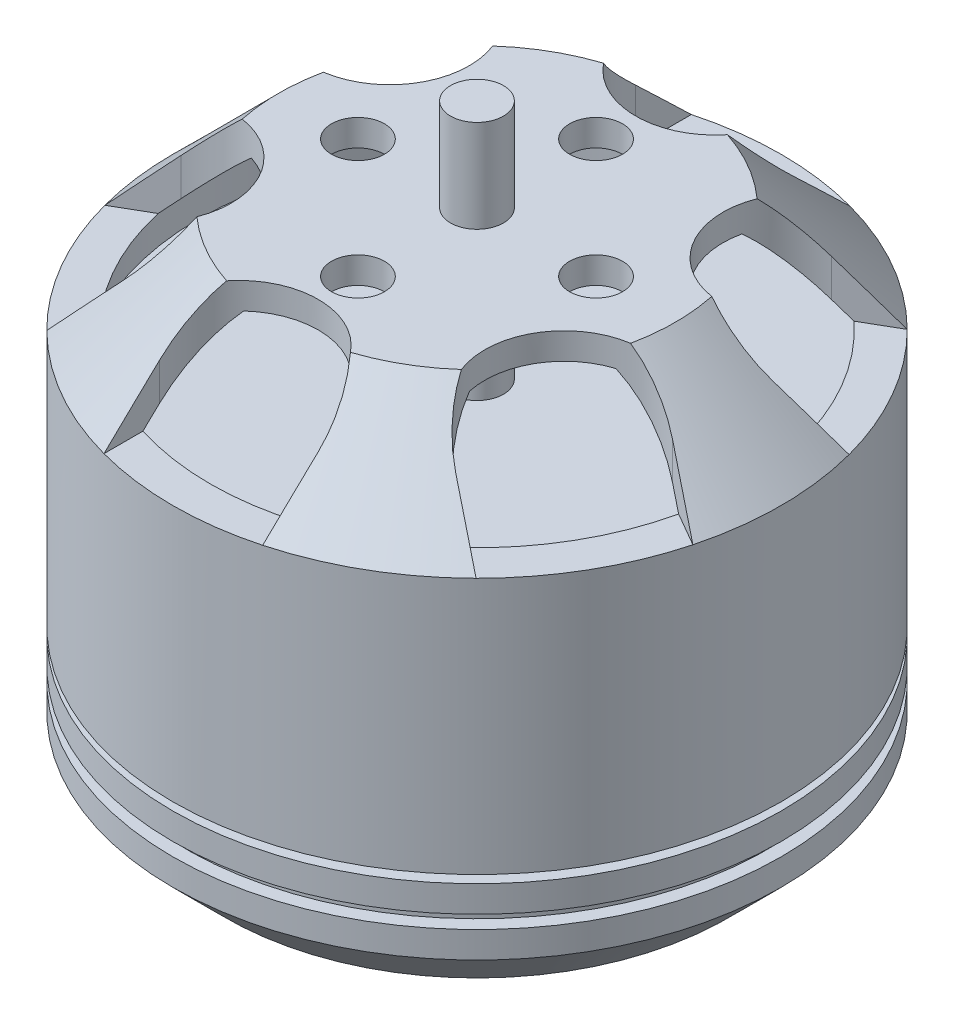
SolidWorks part; units mm, degrees
ref_plane "Front Plane" through (0, 0, 0) normal (0, 0, 1) x (1, 0, 0)
ref_plane "Top Plane" through (0, 0, 0) normal (0, 1, 0) x (1, 0, 0)
ref_plane "Right Plane" through (0, 0, 0) normal (1, 0, 0) x (0, 0, -1)
sketch "Sketch1" plane through (0, 0, 0) normal (0, 0, 1) x (1, 0, 0)
  line L0 (0, 18.8614) -> (0, 0)
  line L1 (1, -3.1386) -> (9.5, -3.1386)
  line L2 (9.5, -3.1386) -> (11.5, -1.1386)
  line L3 (11.5, -1.1386) -> (11.5, -0.1386)
  line L4 (11.5, 11.3614) -> (7.5, 15.3614)
  line L5 (7.5, 15.3614) -> (1, 15.3614)
  line L6 (1, 15.3614) -> (1, 18.8614)
  line L7 (1, 18.8614) -> (0, 18.8614)
  line L8 (0, 0) -> (0, -4.9386)
  line L9 (0, -4.9386) -> (1, -4.9386)
  line L10 (1, -4.9386) -> (1, -3.1386)
  line L11 (2, 14.3614) -> (7.0858, 14.3614)
  line L12 (7.0858, 14.3614) -> (10.5, 10.9472)
  line L13 (10.5, 10.9472) -> (10.5, 9.7543)
  line L14 (10.5, 9.7543) -> (1, 9.7543)
  line L15 (1, 9.7543) -> (1, 13.3614)
  line L16 (1, 13.3614) -> (2, 13.3614)
  line L17 (2, 13.3614) -> (2, 14.3614)
  line L18 (11.5, -0.1386) -> (11, -0.1386)
  line L19 (11, -0.1386) -> (11, 0.3614)
  line L20 (11, 0.3614) -> (11.5, 0.3614)
  line L21 (11.5, 1.3614) -> (9.5, 1.3614)
  line L22 (9.5, 1.3614) -> (9.5, 1.6614)
  line L23 (9.5, 1.6614) -> (11.5, 1.6614)
  line L24 (11.5, 1.6614) -> (11.5, 11.3614)
  line L25 (11.5, 0.3614) -> (11.5, 1.3614)
  dimension "D1" = 23.8
  dimension "D2" = 1.8
  dimension "D3" = 1
  dimension "D4" = 45
  dimension "D5" = 2
  dimension "D6" = 1
  dimension "D7" = 11.5
  dimension "D8" = 3.5
  dimension "D9" = 1
  dimension "D10" = 1
  dimension "D11" = 1
  dimension "D12" = 1
  dimension "D13" = 1
  dimension "D14" = 1
  dimension "D15" = 4
  dimension "D16" = 0.5
  dimension "D17" = 0.5
  dimension "D18" = 1
  dimension "D19" = 2
  dimension "D20" = 0.3
  dimension "D21" = 1
revolve "Revolve2" add sketch "Sketch1" angle 360 about L0
sketch "Sketch2" plane through (0, 15.3614, 0) normal (0, 1, 0) x (1, 0, 0)
  line L0 (0, 0) -> (0, 9) construction
  line L1 (-3, 9) -> (-3, 15.3921)
  line L2 (-3, 15.3921) -> (3, 15.3921)
  line L3 (3, 15.3921) -> (3, 9)
  line L4 (6.2942, 7.0981) -> (11.8299, 10.2941)
  line L5 (11.8299, 10.2941) -> (14.8299, 5.098)
  line L6 (14.8299, 5.098) -> (9.2942, 1.9019)
  line L7 (9.2942, -1.9019) -> (14.8299, -5.098)
  line L8 (14.8299, -5.098) -> (11.8299, -10.2941)
  line L9 (11.8299, -10.2941) -> (6.2942, -7.0981)
  line L10 (3, -9) -> (3, -15.3921)
  line L11 (3, -15.3921) -> (-3, -15.3921)
  line L12 (-3, -15.3921) -> (-3, -9)
  line L13 (-6.2942, -7.0981) -> (-11.8299, -10.2941)
  line L14 (-11.8299, -10.2941) -> (-14.8299, -5.098)
  line L15 (-14.8299, -5.098) -> (-9.2942, -1.9019)
  line L16 (-9.2942, 1.9019) -> (-14.8299, 5.098)
  line L17 (-14.8299, 5.098) -> (-11.8299, 10.2941)
  line L18 (-11.8299, 10.2941) -> (-6.2942, 7.0981)
  circle A0 centre (0, 0) radius 4.5 construction
  circle A1 centre (0, 0) radius 8.5 construction
  circle A2 centre (0, -4.5) radius 1
  circle A3 centre (-4.5, 0) radius 1
  circle A4 centre (0, 4.5) radius 1
  circle A5 centre (4.5, 0) radius 1
  arc A6 (-3, 9) -> (3, 9) centre (0, 9) ccw
  arc A7 (6.2942, 7.0981) -> (9.2942, 1.9019) centre (7.7942, 4.5) ccw
  arc A8 (9.2942, -1.9019) -> (6.2942, -7.0981) centre (7.7942, -4.5) ccw
  arc A9 (3, -9) -> (-3, -9) centre (0, -9) ccw
  arc A10 (-6.2942, -7.0981) -> (-9.2942, -1.9019) centre (-7.7942, -4.5) ccw
  arc A11 (-9.2942, 1.9019) -> (-6.2942, 7.0981) centre (-7.7942, 4.5) ccw
  point P17 (0, 0)
  point P47 (0, 0)
  dimension "D1" = 9
  dimension "D3" = 2
  dimension "D5" = 6
  dimension "D7" = 17
  dimension "D2" = 9
  dimension "D4" = 4
  dimension "D6" = 6
extrude "Cut-Extrude1" cut sketch "Sketch2" against normal blind 4
sketch "Sketch3" plane through (0, -3.1386, 0) normal (0, -1, 0) x (1, 0, 0)
  circle A0 centre (0, 0) radius 6 construction
  circle A1 centre (0, 0) radius 8 construction
  circle A2 centre (0, -6) radius 1
  circle A3 centre (0, 6) radius 1
  circle A4 centre (-8, 0) radius 1
  circle A5 centre (8, 0) radius 1
  dimension "D1" = 16
  dimension "D2" = 12
  dimension "D3" = 2
extrude "Cut-Extrude3" cut sketch "Sketch3" against normal blind 3
